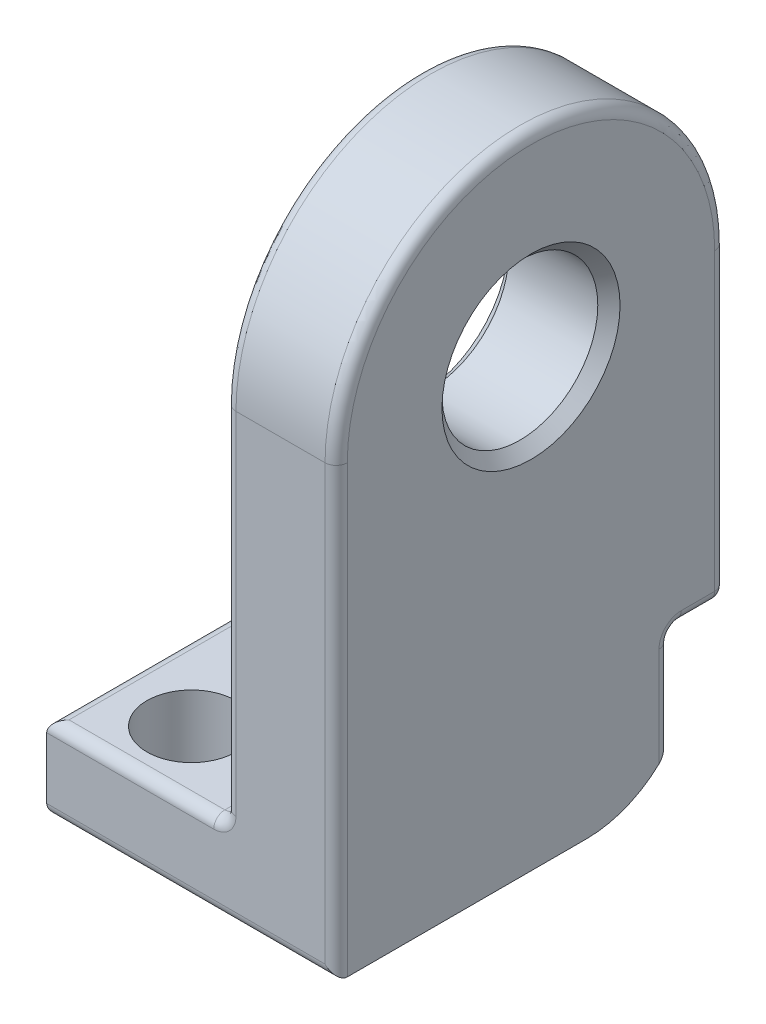
SolidWorks part; units mm, degrees
ref_plane "前视基准面" through (0, 0, 0) normal (0, 0, 1) x (1, 0, 0)
ref_plane "上视基准面" through (0, 0, 0) normal (0, 1, 0) x (1, 0, 0)
ref_plane "右视基准面" through (0, 0, 0) normal (1, 0, 0) x (0, 0, -1)
sketch "草图1" plane through (0, 0, 0) normal (1, 0, 0) x (0, 0, -1)
  line L0 (3.5, 0) -> (3.5, -8)
  line L1 (-3.5, 0) -> (-3.5, -8)
  line L2 (3.5, -8) -> (-3.5, -8)
  circle A0 centre (0, 0) radius 1.4
  arc A1 (3.5, 0) -> (-3.5, 0) centre (0, 0) ccw
  dimension "D1" = 3.5
extrude "凸台-拉伸1" add sketch "草图1" along normal blind 2
sketch "草图2" plane through (0, -8, 0) normal (0, -1, 0) x (1, 0, 0)
  line L0 (2, 3.5) -> (2, -3.5) construction
  line L1 (2, -3.5) -> (-3.2, -3.5)
  line L3 (2, 3.5) -> (-3.2, 3.5)
  line L4 (-3.2, -3.5) -> (-3.2, 3.5)
  line L6 (0, 3.5) -> (0, -3.5) construction
  line L7 (2, -3.5) -> (0, -3.5) construction
  line L8 (2, -3.5) -> (2, 3.5)
  line L9 (2, 3.5) -> (0, 3.5) construction
  circle A0 centre (-1.8, -1.2) radius 0.8
  circle A1 centre (-1.8, 2.3) radius 0.8
  dimension "D1" = 3.2
  dimension "D3" = 1.6
  dimension "D5" = 0
  dimension "D6" = 0
  dimension "D7" = 1.2
  dimension "D8" = 0
  dimension "D2" = 1.8
  dimension "D4" = 4.7
  dimension "D9" = 1.6
  dimension "D10" = 0
extrude "凸台-拉伸2" add sketch "草图2" against normal blind 1.5
sketch "草图5" plane through (0, -8, 0) normal (0, -1, 0) x (1, 0, 0)
  line L0 (2, -3.5) -> (-3.2, -3.5) construction
  line L1 (2, 3.5) -> (2, -3.5) construction
  line L3 (-4, -2.5) -> (2, -2.5)
  line L4 (-4, -2.5) -> (-4, -3.5)
  line L5 (-4, -3.5) -> (2, -3.5)
  line L6 (2, -2.5) -> (2, -3.5)
  dimension "D1" = 0
  dimension "D2" = 1
extrude "切除-拉伸1" cut sketch "草图5" against normal blind 2.5
sketch "草图6" plane through (-3.2, 0, 0) normal (-1, 0, 0) x (0, 0, 1)
  line L0 (0, 0) -> (0, -10.2943) construction
  line L1 (-1, -8.3251) -> (-3.2771, -8.3251)
  line L2 (-3.2771, -6) -> (-2.8974, -6)
  line L6 (-1, -8) -> (-1, -8.3251)
  line L8 (-3.2771, -6) -> (-3.2771, -8.3251)
  arc A1 (-1, -8) -> (-2.8974, -6) centre (-1, -6.1) cw
  point P2 (0, 0)
  point P3 (0, 0)
extrude "切除-拉伸2" cut sketch "草图6" against normal up to next
fillet "圆角1" radius 0.2 1 edges at (0, -6.5, 0.5)
fillet "圆角2" radius 0.2 21 edges at (-3.2, -6.5, 0.5) (2, 3.5, 0) (0, 3.5, 0) (2, -5.5, -3) (0, -5.5, -3) (2, -2.75, -3.5) (2, -4, 3.5) (0, -2.75, -3.5) (0, -3.15, 3.5) (-3.2, -8, 1.25) (-3.2, -7.8067, -1.8349) (-1.7, -6.5, 3.5) (-0.0586, -6.4414, 3.5) (-1.7, -6.5, -2.5) (-0.0586, -6.4414, -2.5) (2, -6.3831, -2.5) (0, -5.9, -2.5) (1, -5.5, -3.5) (-0.6, -8, 3.5) (-0.6, -7.2662, -2.5) (1, -5.5, -2.5)
chamfer "倒角1" distance 0.2 angle 45 2 edges at (0, 0, -1.4) (2, 0, -1.4)
